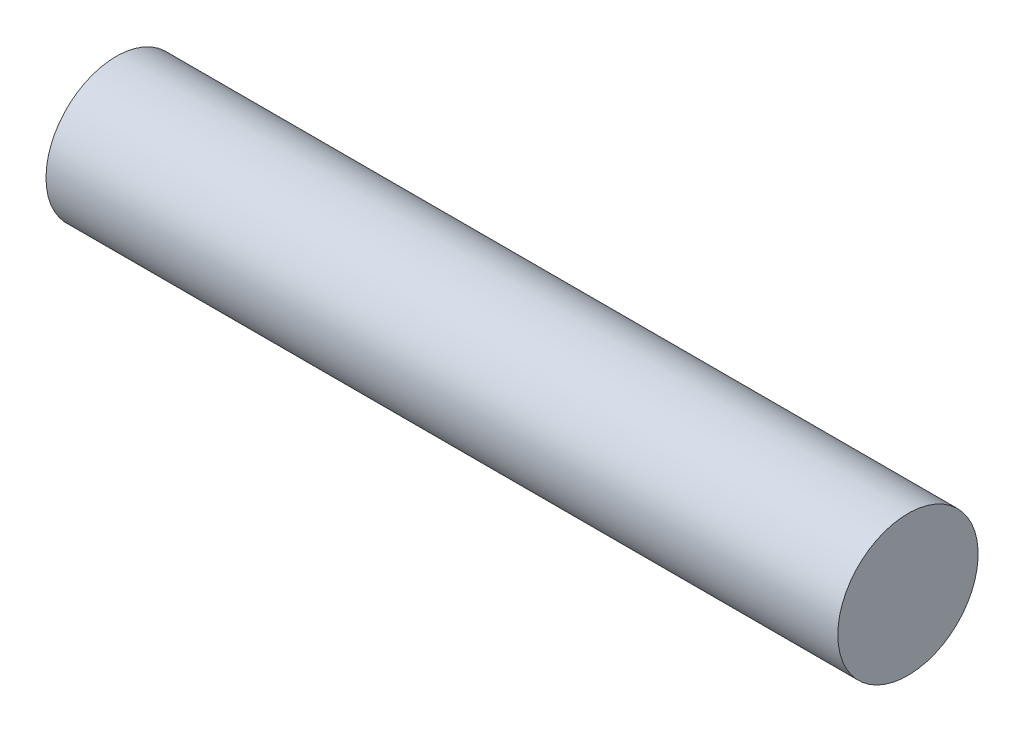
SolidWorks part; units mm, degrees
ref_plane "前视基准面" through (0, 0, 0) normal (0, 0, 1) x (1, 0, 0)
ref_plane "上视基准面" through (0, 0, 0) normal (0, 1, 0) x (1, 0, 0)
ref_plane "右视基准面" through (0, 0, 0) normal (1, 0, 0) x (0, 0, -1)
other "Configuration Table"
sketch "草图1" plane through (0, 0, 0) normal (0, 0, 1) x (1, 0, 0)
  line L0 (0, 0) -> (40.0305, 0) construction
  line L1 (0, 0) -> (0, 7)
  line L2 (0, 7) -> (79, 7)
  line L3 (79, 7) -> (79, 0)
  line L4 (0, 0) -> (79, 0)
  dimension "D1" = 7
  dimension "D2" = 79
revolve "旋转1" add sketch "草图1" angle 360 about L0
